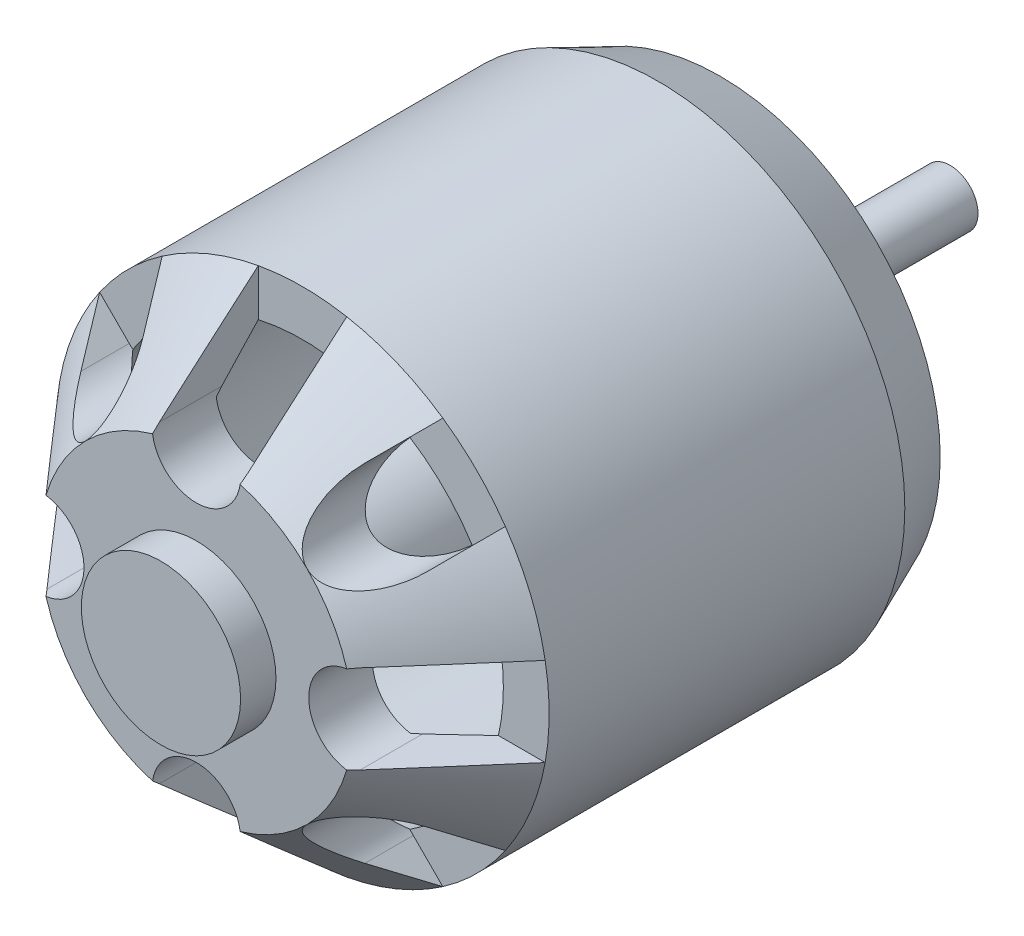
SolidWorks part; units mm, degrees
ref_plane "前视基准面" through (0, 0, 0) normal (0, 0, 1) x (1, 0, 0)
ref_plane "上视基准面" through (0, 0, 0) normal (0, 1, 0) x (1, 0, 0)
ref_plane "右视基准面" through (0, 0, 0) normal (1, 0, 0) x (0, 0, -1)
sketch "草图1" plane through (0, 0, 0) normal (0, 0, 1) x (1, 0, 0)
  circle A0 centre (0, 0) radius 13.94
extrude "凸台-拉伸1" add sketch "草图1" along normal blind 31.6
sketch "草图2" plane through (0, 0, 31.6) normal (0, 0, 1) x (1, 0, 0)
  circle A0 centre (0, 0) radius 11.35
extrude "切除-拉伸1" cut sketch "草图2" against normal blind 27 contours A0
sketch "草图3" plane through (0, 0, 31.6) normal (0, 0, 1) x (1, 0, 0)
  circle A0 centre (0, 0) radius 13.94 construction
  circle A1 centre (0, 0) radius 13.94
extrude "切除-拉伸2" cut sketch "草图3" against normal blind 8
sketch "草图4" plane through (0, 0, 23.6) normal (0, 0, 1) x (1, 0, 0)
  circle A0 centre (0, 0) radius 4.5
extrude "凸台-拉伸2" add sketch "草图4" along normal blind 8 and the other way up to next
ref_plane "基准面1" through (0, 0, 29.6) normal (0, 0, 1) x (1, 0, 0)
sketch "草图5" plane through (0, 0, 29.6) normal (0, 0, 1) x (1, 0, 0)
  circle A0 centre (0, 0) radius 8.85
extrude "凸台-拉伸3" add sketch "草图5" against normal blind 3.6
sketch "草图6" plane through (0, 0, 0) normal (0, 1, 0) x (1, 0, 0)
  line L4 (-13.94, -23.6) -> (13.94, -23.6) construction
  line L5 (13.94, -23.6) -> (8.85, -29.6)
  line L6 (-8.85, -29.6) -> (8.85, -29.6) construction
  line L7 (8.85, -29.6) -> (8.85, -26)
  line L8 (8.85, -26) -> (-8.85, -26) construction
  line L9 (8.85, -26) -> (11.35, -23.6)
  line L10 (13.94, -23.6) -> (11.35, -23.6)
revolve "旋转1" add sketch "草图6" angle 360 about axis through (0, 0, -500000) along (0, 0, 1)
sketch "草图7" plane through (0, 0, 29.6) normal (0, 0, 1) x (1, 0, 0)
  line L0 (-8.85, 2.5) -> (-13.714, 2.5)
  line L1 (-8.85, -2.5) -> (-13.714, -2.5)
  arc A0 (-8.85, -2.5) -> (-8.85, 2.5) centre (-8.85, 0) ccw
  circle A1 centre (0, 0) radius 8.85 construction
  circle A2 centre (0, 0) radius 13.94 construction
  arc A3 (-13.714, 2.5) -> (-13.714, -2.5) centre (0, 0) ccw
extrude "切除-拉伸3" cut sketch "草图7" against normal blind 6
pattern_circular "阵列(圆周)1" count 4 over 360 about axis through (0, 0, 0) along (0, 0, 1) of "切除-拉伸3"
sketch "草图9" plane through (0, 0, 29.6) normal (0, 0, 1) x (1, 0, 0)
  line L0 (0, 0) -> (-13.94, 0)
  line L8 (-9.7934, 6.2579) -> (-11.465, 7.9295)
  line L9 (-6.2579, 9.7934) -> (-7.9295, 11.465)
  arc A0 (-13.714, 2.5) -> (-13.714, -2.5) centre (0, 0) ccw construction
  arc A2 (-7.9295, 11.465) -> (-11.465, 7.9295) centre (0, 0) ccw
  arc A3 (-9.7934, 6.2579) -> (-6.2579, 9.7934) centre (-8.0257, 8.0257) ccw
  arc A4 (-2.5, 13.714) -> (-13.714, 2.5) centre (0, 0) ccw construction
extrude "切除-拉伸4" cut sketch "草图9" against normal blind 6 contours L8 A3 L9 A2
pattern_circular "阵列(圆周)2" count 4 over 360 about axis through (0, 0, 0) along (0, 0, 1) of "切除-拉伸4"
sketch "草图12" plane through (0, 0, 0) normal (0, 0, -1) x (-1, 0, 0)
  circle A0 centre (0, 0) radius 1.575
extrude "凸台-拉伸4" add sketch "草图12" along normal blind 13
chamfer "倒角1" distance 1.5 distance2 3.5 1 edges at (13.94, 0, 0)
